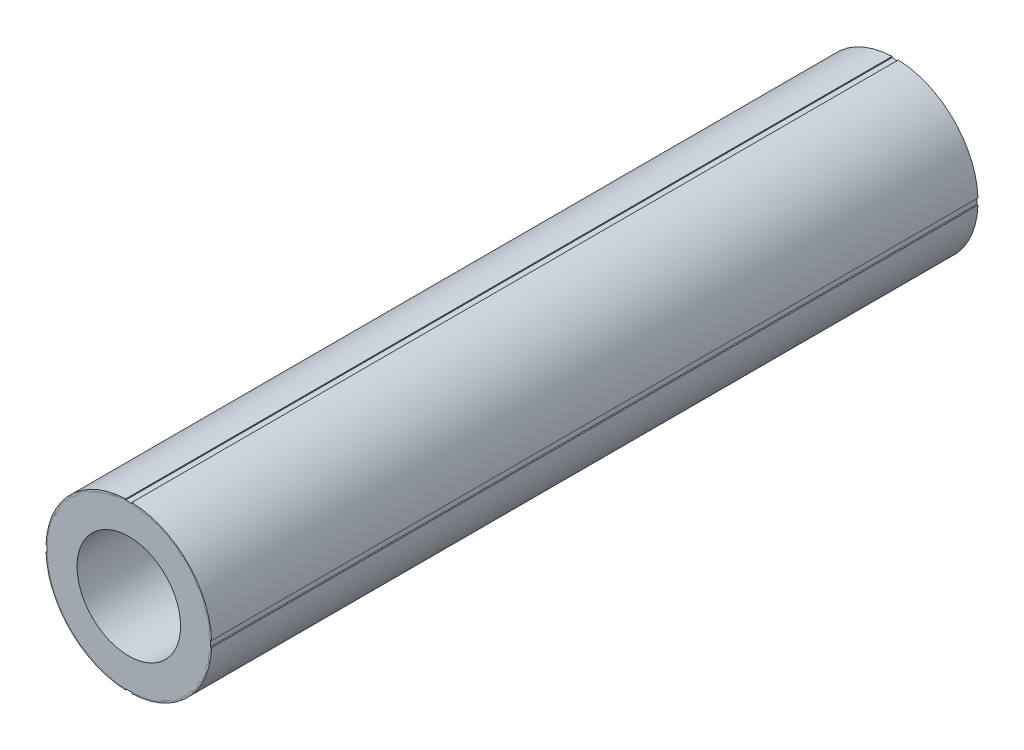
SolidWorks part; units mm, degrees
ref_plane "Front Plane" through (0, 0, 0) normal (0, 0, 1) x (1, 0, 0)
ref_plane "Top Plane" through (0, 0, 0) normal (0, 1, 0) x (1, 0, 0)
ref_plane "Right Plane" through (0, 0, 0) normal (1, 0, 0) x (0, 0, -1)
sketch "Sketch1" plane through (0, 0, 0) normal (0, 0, 1) x (1, 0, 0)
  circle A0 centre (0, 0) radius 0.4
  circle A1 centre (0, 0) radius 0.39
  dimension "D1" = 0.8
  dimension "D2" = 0.78
extrude "External Electrode" add sketch "Sketch1" along normal blind 3.7
sketch "Sketch3" plane through (0, 0, 0) normal (0, 0, 1) x (1, 0, 0)
  line L1 (-0.015, -0.5) -> (0.015, -0.5)
  line L2 (-0.015, -0.5) -> (-0.015, 0.5)
  line L3 (-0.015, 0.5) -> (0.015, 0.5)
  line L4 (0.015, -0.5) -> (0.015, 0.5)
  line L5 (-0.015, -0.5) -> (0.015, 0.5) construction
  line L6 (-0.015, 0.5) -> (0.015, -0.5) construction
  line L7 (0.5, -0.015) -> (-0.5, -0.015)
  line L8 (0.5, -0.015) -> (0.5, 0.015)
  line L9 (0.5, 0.015) -> (-0.5, 0.015)
  line L10 (-0.5, -0.015) -> (-0.5, 0.015)
  line L11 (0.5, -0.015) -> (-0.5, 0.015) construction
  line L12 (0.5, 0.015) -> (-0.5, -0.015) construction
  point P0 (0, 0)
  point P6 (0, 0)
  circle M16 centre (0, 0) radius 0.39
  dimension "D1" = 0.03
  dimension "D2" = 0.03
  dimension "D3" = 1
  dimension "D4" = 1
extrude "Cuts" cut sketch "Sketch3" along normal blind 3.7 contours L2 L9 M16 | L9 L4 M16 | L7 L4 M16 | L7 L2 M16
sketch "Sketch5" plane through (0, 0, 0) normal (0, 0, 1) x (1, 0, 0)
  circle A0 centre (0, 0) radius 0.395
  circle A1 centre (0, 0) radius 0.255
  dimension "D1" = 0.51
  dimension "D2" = 0.79
extrude "PZT Tube" add sketch "Sketch5" along normal blind 3.7 separate body
sketch "Sketch7" plane through (0, 0, 3.7) normal (0, 0, 1) x (1, 0, 0)
  circle A0 centre (0, 0) radius 0.255
  circle A1 centre (0, 0) radius 0.25
  dimension "D1" = 0.5
  dimension "D2" = 0.51
extrude "Internal Electrode" add sketch "Sketch7" against normal blind 3.7
